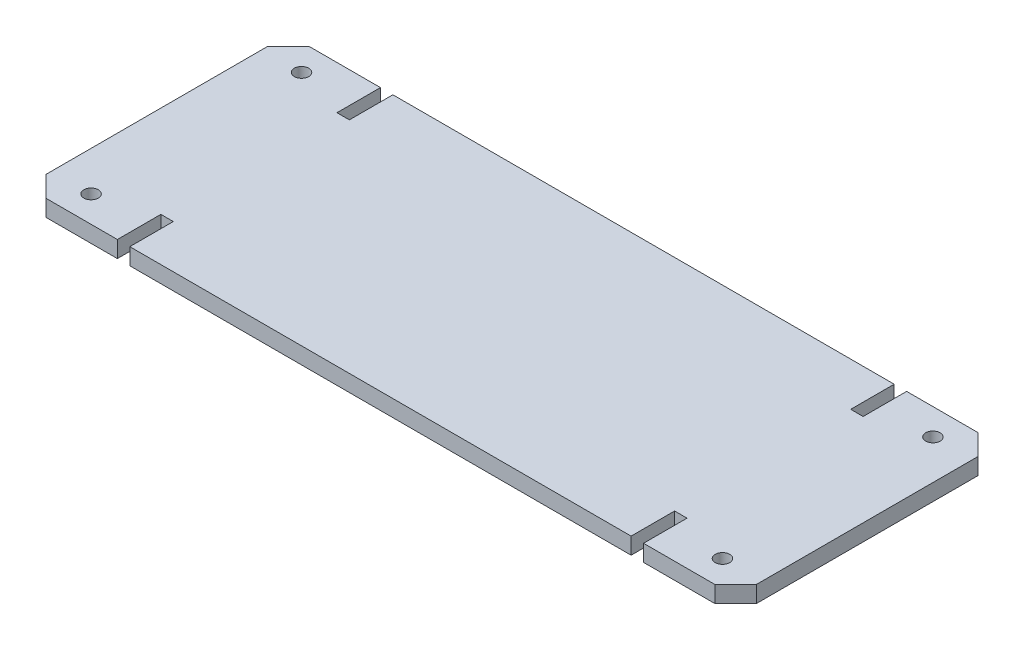
SolidWorks part; units mm, degrees
ref_plane "Front Plane" through (0, 0, 0) normal (0, 0, 1) x (1, 0, 0)
ref_plane "Top Plane" through (0, 0, 0) normal (0, 1, 0) x (1, 0, 0)
ref_plane "Right Plane" through (0, 0, 0) normal (1, 0, 0) x (0, 0, -1)
sketch "Sketch1" plane through (0, 0, 0) normal (0, 1, 0) x (1, 0, 0)
  line L1 (-85.725, -31.75) -> (85.725, -31.75)
  line L2 (-85.725, -31.75) -> (-85.725, 31.75)
  line L3 (-85.725, 31.75) -> (85.725, 31.75)
  line L4 (85.725, -31.75) -> (85.725, 31.75)
  line L5 (-85.725, -31.75) -> (85.725, 31.75) construction
  line L6 (-85.725, 31.75) -> (85.725, -31.75) construction
  circle A0 centre (-76.2, 25.4) radius 1.75
  circle A1 centre (-76.2, -25.4) radius 1.75
  circle A2 centre (76.2, 25.4) radius 1.75
  circle A3 centre (76.2, -25.4) radius 1.75
  point P0 (0, 0)
  dimension "D3" = 3.5
  dimension "D4" = 3.5
  dimension "D5" = 3.5
  dimension "D6" = 3.5
  dimension "D7" = 152.4
  dimension "D8" = 152.4
  dimension "D9" = 50.8
  dimension "D10" = 50.8
  dimension "D11" = 6.35
  dimension "D12" = 9.525
  dimension "D13" = 9.525
  dimension "D14" = 6.35
  dimension "D1" = 171.45
  dimension "D2" = 63.5
extrude "Boss-Extrude1" add sketch "Sketch1" along normal blind 4
chamfer "Chamfer1" distance 5 angle 45 4 edges at (-85.725, 2, 31.75) (-85.725, 2, -31.75) (85.725, 2, -31.75) (85.725, 2, 31.75)
sketch "Sketch3" plane through (0, 4, 0) normal (0, 1, 0) x (1, 0, 0)
  line L0 (-80.725, -31.75) -> (80.725, -31.75) construction
  line L1 (63.5, -31.75) -> (60.5, -31.75)
  line L2 (63.5, -31.75) -> (63.5, -21.25)
  line L3 (63.5, 31.75) -> (60.5, 31.75)
  line L4 (60.5, -31.75) -> (60.5, -21.25)
  line L5 (80.725, 31.75) -> (-80.725, 31.75) construction
  line L6 (-85.725, 26.75) -> (-85.725, -26.75) construction
  line L7 (-63.5, -31.75) -> (-60.5, -31.75)
  line L8 (-63.5, -31.75) -> (-63.5, -21.25)
  line L9 (-63.5, 31.75) -> (-60.5, 31.75)
  line L10 (-60.5, -31.75) -> (-60.5, -21.25)
  line L11 (85.725, -26.75) -> (85.725, 26.75) construction
  line L12 (60.5, 21.25) -> (60.5, 31.75)
  line L13 (63.5, -21.25) -> (60.5, -21.25)
  line L14 (-63.5, 21.25) -> (-63.5, 31.75)
  line L15 (63.5, 21.25) -> (60.5, 21.25)
  line L16 (-60.5, 21.25) -> (-60.5, 31.75)
  line L17 (-60.5, -21.25) -> (-63.5, -21.25)
  line L19 (-60.5, 21.25) -> (-63.5, 21.25)
  line L21 (63.5, 21.25) -> (63.5, 31.75)
  dimension "D1" = 3
  dimension "D2" = 3
  dimension "D3" = 22.225
  dimension "D4" = 22.225
  dimension "D5" = 10.5
  dimension "D6" = 10.5
  dimension "D7" = 10.5
  dimension "D8" = 10.5
extrude "Cut-Extrude2" cut sketch "Sketch3" against normal blind 4
